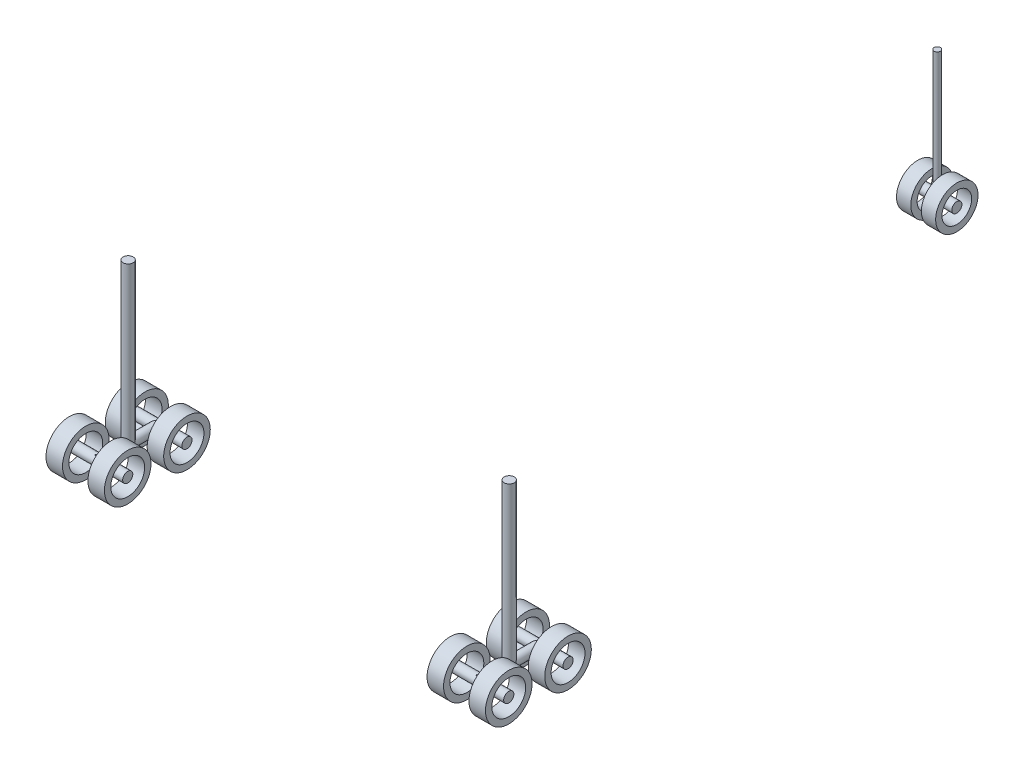
SolidWorks part; units mm, degrees
other "DetailItem1" parameters "RD1"=24.5989, "RD3"=24384, "RD4"=17538.8642, "RD5"=2725.3831, "RD6"=31107.4169, "RD7"=56568.0005, "RD2"=22.452, "RD8"=19.396
ref_plane "Front Plane" through (0, 0, 0) normal (0, 0, 1) x (1, 0, 0)
ref_plane "Top Plane" through (0, 0, 0) normal (0, 1, 0) x (1, 0, 0)
ref_plane "Right Plane" through (0, 0, 0) normal (1, 0, 0) x (0, 0, -1)
sketch "Sketch2" plane through (0, 0, 0) normal (0, 1, 0) x (1, 0, 0)
  line L0 (0, -6122.228) -> (0, 2040.7427)
  line L1 (0, 0) -> (-18096.1342, 0) construction
  line L2 (0, 0) -> (-21640.8, -16307.5125) construction
  line L3 (-21640.8, -18450.2946) -> (-21640.8, -15593.2518)
  line L4 (-21640.8, -15593.2518) -> (0, 2040.7427)
  line L5 (-21640.8, -18450.2946) -> (0, -6122.228)
  line L6 (-9083.802, -5361.1886) -> (-9083.802, -6845.1358) construction
  line L7 (-9083.802, -6845.1358) -> (-9083.802, -11296.9774) construction
  line L8 (-9083.802, -6845.1358) -> (0, -6845.1358) construction
  line L9 (0, 408.1485) -> (-18440.4, -13713.752)
  line L10 (0, -35661.6) -> (-7316.724, -42249.6079) construction
  line L11 (0, -35661.6) -> (-8167.6786, -35661.6) construction
  line L12 (0, -34539.0879) -> (0, -39029.1363)
  line L13 (-7316.724, -43428.2455) -> (-7316.724, -41856.7287)
  line L14 (-7316.724, -41856.7287) -> (0, -34539.0879)
  line L15 (0, -39029.1363) -> (-7316.724, -43428.2455)
  line L16 (-2544.3607, -37083.7674) -> (-2544.3607, -37952.5526) construction
  line L17 (-2544.3607, -37952.5526) -> (-2544.3607, -40558.9084) construction
  line L18 (-2544.3607, -37952.5526) -> (0, -37952.5526) construction
  line L19 (-18440.4, -13713.752) -> (-18440.4, -15898.787)
  line L20 (-18440.4, -15898.787) -> (0, -4489.6339)
  line L21 (0, 408.1485) -> (0, -4489.6339) construction
  line L22 (0, -4489.6339) -> (0, 408.1485) construction
  line L23 (0, 408.1485) -> (0, -2040.7427) construction
  line L24 (0, 408.1485) -> (0, -4489.6339) construction
  line L25 (0, -2040.7427) -> (-18440.4, -14806.2695) construction
  line L26 (0, 408.1485) -> (-21640.8, -16164.6603) construction
  line L27 (-6975.7046, -4933.9377) -> (-6975.7046, -6869.7347) construction
  line L28 (-6975.7046, -6869.7347) -> (-6975.7046, -8805.5317) construction
  line L29 (-6975.7046, -6869.7347) -> (0, -6869.7347) construction
  dimension "Wing Sweep" = 37
  dimension "Half Span" = 21640.8
  dimension "Wing Root" = 8162.9707
  dimension "D4" = 2040.7427
  dimension "Wing Tip" = 2857.0428
  dimension "D6" = 714.2607
  dimension "Wing YBar" = 9083.802
  dimension "Tail Sweep" = 42
  dimension "Tail Root" = 4490.0484
  dimension "D10" = 1122.5121
  dimension "Tail Tip" = 1571.5168
  dimension "D12" = 392.8792
  dimension "D13" = 7316.724
  dimension "Tail Ybar" = 2544.3607
  dimension "First Spar" = 1632.5941
  dimension "Second Spar" = 6530.3766
  dimension "Fuel Tip" = 2185.035
  dimension "Tip Spar" = 571.4086
  dimension "Fuel Ybar" = 6975.7046
  dimension "Fuel Tank Length" = 18440.4
  dimension "Tail Arm" = 35661.6
sketch "Sketch4" plane through (0, 0, 0) normal (0, 1, 0) x (1, 0, 0)
  line L0 (0, 17538.8642) -> (0, -40677.9358) construction
  line L1 (-2194.56, 17538.8642) -> (2194.56, 17538.8642) construction
  line L2 (-2194.56, 10955.1842) -> (-2194.56, -31899.6958)
  line L3 (-2194.56, -40677.9358) -> (2194.56, -40677.9358) construction
  line L4 (2194.56, 10955.1842) -> (2194.56, -31899.6958)
  line L5 (0, -6122.228) -> (0, 2040.7427) construction
  line L6 (-9083.802, -6845.1358) -> (0, -6845.1358) construction
  line L7 (-2544.3607, -37952.5526) -> (0, -37952.5526) construction
  line L8 (0, 0) -> (-21640.8, -16307.5125) construction
  line L9 (-21640.8, -15593.2518) -> (0, 2040.7427) construction
  line L10 (-8474.964, 1555.5245) -> (-5807.964, 1555.5245)
  line L11 (-8474.964, 1555.5245) -> (-8474.964, -5453.2245)
  line L12 (-8474.964, -5453.2245) -> (-5807.964, -5453.2245)
  line L13 (-5807.964, 1555.5245) -> (-5807.964, -5453.2245)
  line L14 (2194.56, 10955.1842) -> (-2194.56, 10955.1842)
  arc A0 (-2194.56, -31899.6958) -> (2194.56, -31899.6958) centre (0, -31899.6958) ccw construction
  spline S0 degree 2 poles (-2194.56, 10955.1842) (-2319.3121, 14550.827) (0, 17538.8642) knots 0 0 0 1 1 1 construction
  spline S1 degree 2 poles (2194.56, 10955.1842) (2319.3121, 14550.827) (0, 17538.8642) knots 0 0 0 1 1 1 construction
  spline S2 degree 3 poles (-2194.56, -31899.6958) (-2185.0252, -17343.0176) (-1882.3736, -55849.4008) (-475.0937, -22625.7195) (0, -39029.1363) knots 0 0 0 0 0.566127 1 1 1 1 construction
  spline S3 degree 3 poles (2194.56, -31899.6958) (2185.0252, -17343.0176) (1882.3736, -55849.4008) (475.0937, -22625.7195) (0, -39029.1363) knots 0 0 0 0 0.566127 1 1 1 1 construction
  spline S4 degree 2 poles (-2194.56, -31899.6958) (-4104.2514, -24790.3016) (0, -27753.3552) knots 0 0 0 1 1 1
  spline S5 degree 2 poles (2194.56, -31899.6958) (4104.2514, -24790.3016) (0, -27753.3552) knots 0 0 0 1 1 1
  point P6 (0, 10955.1842)
  point P7 (0, -31899.6958)
  point P8 (0, -6845.1358)
  point P15 (0, -34094.2558)
  point P28 (-7141.464, 1555.5245)
  point P29 (-7141.464, -3778.4755)
  point P35 (-7141.464, -5381.4791)
  point P43 (0, -1968.3358)
  point P44 (-7141.464, -1247.9751)
  dimension "Fuse Length" = 58216.8
  dimension "Fuse Dia" = 4389.12
  dimension "D3" = 6583.68
  dimension "D4" = 8778.24
  dimension "D6" = 7141.464
  dimension "Engine Dia" = 2667
  dimension "Engine Length" = 7008.749
  dimension "D9" = 5334
  dimension "D10" = 2803.4996
  dimension "D11" = 5597.1607
  dimension "D2" = 19507.2
ref_plane "Plane1" through (0, 609.6, 0) normal (0, 1, 0) x (1, 0, 0)
sketch "Sketch10" plane through (0, 0, 0) normal (0, 1, 0) x (1, 0, 0)
  line L0 (-21640.8, -15593.2518) -> (-2194.56, 252.5066)
  line L1 (-2194.56, 10955.1842) -> (-2194.56, -31899.6958) construction
  line L2 (-21640.8, -15593.2518) -> (-21640.8, -18450.2946)
  line L3 (-21640.8, -18450.2946) -> (-7141.464, -10190.49)
  line L4 (-7141.464, -10190.49) -> (-2194.56, -10190.49)
  line L5 (-21640.8, -18450.2946) -> (0, -6122.228) construction
  line L6 (-21640.8, -15593.2518) -> (0, 2040.7427) construction
  line L7 (-2194.56, -10190.49) -> (-2194.56, 252.5066) construction
  line L9 (0, 271.2873) -> (0, -10190.49)
  line L10 (0, -10190.49) -> (-2194.56, -10190.49)
  line L11 (0, -6122.228) -> (0, 2040.7427) construction
  line L12 (-2194.56, 252.5066) -> (0, 2040.7427)
  line L13 (0, 2040.7427) -> (0, 271.2873)
sketch "Sketch11" plane through (0, 0, 0) normal (0, 1, 0) x (1, 0, 0)
  line L0 (0, 17538.8642) -> (0, -40677.9358) construction
  point P0 (0, -3278.9758)
  dimension "D1" = 20817.84
ref_plane "Plane3" through (0, 1731.482, 0) normal (0, 1, 0) x (1, 0, 0)
sketch "Sketch12" plane through (0, 0, 0) normal (0, 1, 0) x (1, 0, 0)
  line L0 (0, 17538.8642) -> (0, -40677.9358) construction
  line L1 (-127, 11129.9847) -> (127, 11129.9847) construction
  line L2 (-127, 11129.9847) -> (-127, 10780.3837) construction
  line L3 (-127, 10780.3837) -> (127, 10780.3837) construction
  line L4 (127, 11129.9847) -> (127, 10780.3837) construction
  line L5 (-127, 11129.9847) -> (127, 10780.3837) construction
  line L6 (-127, 10780.3837) -> (127, 11129.9847) construction
  line L7 (-4572, -3888.5758) -> (0, 10955.1842) construction
  line L8 (-4876.8, -3469.0546) -> (-4267.2, -3469.0546) construction
  line L9 (-4876.8, -3469.0546) -> (-4876.8, -4308.097) construction
  line L10 (-4876.8, -4308.097) -> (-4267.2, -4308.097) construction
  line L11 (-4267.2, -3469.0546) -> (-4267.2, -4308.097) construction
  line L12 (-4876.8, -3469.0546) -> (-4267.2, -4308.097) construction
  line L13 (-4876.8, -4308.097) -> (-4267.2, -3469.0546) construction
  line L14 (-4572, -3888.5758) -> (0, -3888.5758) construction
  line L15 (-4572, -3888.5758) -> (0, -5296.7893) construction
  line L16 (-4572, -3469.0546) -> (-4572, -4308.097) construction
  line L17 (-4572, -3888.5758) -> (-762, -3888.5758) construction
  line L19 (-1389.4421, -4752.1758) -> (-134.5579, -4752.1758) construction
  line L20 (-1389.4421, -4752.1758) -> (-1389.4421, -3024.9758) construction
  line L21 (-1389.4421, -3024.9758) -> (-134.5579, -3024.9758) construction
  line L22 (-134.5579, -4752.1758) -> (-134.5579, -3024.9758) construction
  line L23 (-1389.4421, -4752.1758) -> (-134.5579, -3024.9758) construction
  line L24 (-1389.4421, -3024.9758) -> (-134.5579, -4752.1758) construction
  circle A0 centre (-4572, -3888.5758) radius 121.92
  circle A1 centre (-1389.4421, -4752.1758) radius 711.2 construction
  circle A4 centre (-1389.4421, -3024.9758) radius 711.2 construction
  point P0 (0, 10955.1842)
  point P7 (-4572, -3888.5758)
  point P30 (-1389.4421, -3736.1758)
  point P31 (-1389.4421, -4040.9758)
  point P39 (-762, -3888.5758)
  dimension "D8" = 243.84
  dimension "D9" = 304.8
  dimension "D11" = 1422.4
  dimension "D1" = 4572
  dimension "D2" = 90
  dimension "D3" = 36
  dimension "D4" = 36
  dimension "D5" = 254
  dimension "D6" = 609.6
  dimension "D7" = 609.6
  dimension "D10" = 36
  dimension "D12" = 3810
ref_plane "Plane2" through (-4572, 0, 3888.5758) normal (0.2944, 0, -0.9557) x (-0.9557, 0, -0.2944)
sketch "Sketch13" plane through (0, 1731.482, 0) normal (0, 1, 0) x (1, 0, 0)
  line L1 (0, -6122.228) -> (0, 2040.7427) construction
  point P0 (0, -3278.9758)
  dimension "D1" = 0
sketch "Sketch14" plane through (-4572, 0, 3888.5758) normal (0.2944, 0, -0.9557) x (-0.9557, 0, -0.2944)
  line L0 (0, 0) -> (-4189.9906, 1731.482) construction
  line L1 (0, 0) -> (-5277.159, 0) construction
  dimension "D1" = 22.452
ref_plane "Plane4" through (-4572, 0, 0) normal (-1, 0, 0) x (0, 0, 1)
sketch "Sketch15" plane through (-4572, 0, 0) normal (-1, 0, 0) x (0, 0, 1)
  line L0 (3888.5758, 0) -> (3278.9758, 1731.482) construction
  line L1 (3888.5758, 0) -> (3888.5758, 1731.482) construction
ref_plane "Plane5" through (-4876.8, 0, 0) normal (1, 0, 0) x (0, 0, -1)
sketch "Sketch16" plane through (-4876.8, 0, 0) normal (1, 0, 0) x (0, 0, -1)
  line L0 (-3888.5758, 0) -> (-3177.3758, 0) construction
  line L2 (-3888.5758, 0) -> (-3888.5758, 631.3043) construction
  line L3 (-3888.5758, 0) -> (-4599.7758, 0) construction
  circle A0 centre (-3177.3758, 0) radius 558.8
  circle A1 centre (-4599.7758, 0) radius 558.8
  circle A3 centre (-3177.3758, 0) radius 406.4
  circle A4 centre (-4599.7758, 0) radius 406.4
  point P3 (-4040.9758, 0)
  point P8 (-3888.5758, 0)
  point P9 (-3736.1758, 0)
  dimension "D1" = 1117.6
  dimension "D3" = 812.8
  dimension "D2" = 304.8
extrude "Boss-Extrude1" add sketch "Sketch16" against normal blind 396.24
ref_plane "Plane6" through (-4572, 0, 0) normal (1, 0, 0) x (0, 0, -1)
mirror "Mirror2" about plane through (-4572, 0, 0) normal (1, 0, 0) of bodies 132 133
extrude "Boss-Extrude2" add sketch "Sketch12" along normal blind 3810
sketch "Sketch17" plane through (-5273.04, 0, 0) normal (-1, 0, 0) x (0, 0, 1)
  circle A0 centre (3177.3758, 0) radius 121.92
  circle A1 centre (3177.3758, 0) radius 406.4 construction
  circle A2 centre (4599.7758, 0) radius 121.92
  circle A3 centre (4599.7758, 0) radius 406.4 construction
  dimension "D1" = 243.84
extrude "Boss-Extrude3" add sketch "Sketch17" against normal up to surface (1402.08 mm away) separate body up to face at (-3870.96, 0, 5006.1758)
ref_plane "Plane7" through (0, 0, 3888.5758) normal (0, 0, 1) x (1, 0, 0)
sketch "Sketch18" plane through (0, 0, 3888.5758) normal (0, 0, 1) x (1, 0, 0)
  circle A0 centre (-4572, 0) radius 121.92
  dimension "D1" = 243.84
extrude "Boss-Extrude4" add sketch "Sketch18" along normal blind 762 and the other way blind 762
ref_plane "Plane8" through (-127, 0, 0) normal (1, 0, 0) x (0, 0, -1)
sketch "Sketch19" plane through (-127, 0, 0) normal (1, 0, 0) x (0, 0, -1)
  line L0 (11129.9847, 0) -> (10780.3837, 0) construction
  circle A0 centre (10955.1842, 0) radius 508
  circle A1 centre (10955.1842, 0) radius 355.6
  dimension "D1" = 1016
  dimension "D2" = 711.2
extrude "Boss-Extrude5" add sketch "Sketch19" against normal blind 342.9 separate body
mirror "Mirror4" about plane through (0, 0, 0) normal (1, 0, 0) of bodies 141 133 132 135 140 134
sketch "Sketch20" plane through (-469.9, 0, 0) normal (-1, 0, 0) x (0, 0, 1)
  circle A0 centre (-10955.1842, 0) radius 121.92
  circle A1 centre (3177.3758, 0) radius 121.92 construction
  circle A2 centre (-10955.1842, 0) radius 355.6 construction
extrude "Boss-Extrude6" add sketch "Sketch20" against normal up to surface (939.8 mm away) separate body up to face at (469.9, 0, -11310.7842)
sketch "Sketch21" plane through (0, 0, 0) normal (0, 1, 0) x (1, 0, 0)
  circle A0 centre (0, 10955.1842) radius 76.2
extrude "Boss-Extrude7" add sketch "Sketch21" along normal blind 3048
sketch "Sketch23" plane through (0, 3810, 0) normal (0, 1, 0) x (1, 0, 0)
  circle A0 centre (0, -3278.9758) radius 469.6531 construction
  point P0 (0, -3278.9758)
  point P3 (0, -3278.9758)
sketch "Sketch24" plane through (-469.9, 0, 0) normal (-1, 0, 0) x (0, 0, 1)
  line L0 (-10955.1842, 0) -> (-10955.1842, 3048) construction
  line L1 (-10878.9842, 3048) -> (-11031.3842, 3048) construction
sketch "Sketch25" plane through (0, 0, 0) normal (0, 1, 0) x (1, 0, 0)
  line L0 (-762, -4015.5758) -> (-762, -3761.5758) construction
  line L1 (-4572, -3888.5758) -> (0, -3888.5758) construction
  line L2 (-762, -3888.5758) -> (-4572, -3888.5758) construction
  line L3 (0, -2402.84) -> (0, 2402.84) construction
  line L4 (762, -3888.5758) -> (4572, -3888.5758) construction
  line L5 (762, -4015.5758) -> (762, -3761.5758) construction
  line L6 (0, 10955.1842) -> (0, 14003.1842) construction
  line L7 (-298.45, 14003.1842) -> (0, 14003.1842) construction
  line L8 (0, 14003.1842) -> (298.45, 14003.1842) construction
  line L9 (127, 14511.1842) -> (127, 13495.1842) construction
  line L10 (127, 14511.1842) -> (469.9, 14511.1842) construction
  line L11 (127, 13495.1842) -> (469.9, 13495.1842) construction
  line L12 (469.9, 14511.1842) -> (469.9, 13495.1842) construction
  line L13 (127, 14511.1842) -> (469.9, 13495.1842) construction
  line L14 (127, 13495.1842) -> (469.9, 14511.1842) construction
  line L15 (-127, 14511.1842) -> (-127, 13495.1842) construction
  line L16 (-127, 14511.1842) -> (-469.9, 14511.1842) construction
  line L17 (-127, 13495.1842) -> (-469.9, 13495.1842) construction
  line L18 (-469.9, 14511.1842) -> (-469.9, 13495.1842) construction
  line L19 (-127, 14511.1842) -> (-469.9, 13495.1842) construction
  line L20 (-127, 13495.1842) -> (-469.9, 14511.1842) construction
  circle A0 centre (-762, -3202.7758) radius 558.8 construction
  circle A1 centre (-762, -4574.3758) radius 558.8 construction
  circle A2 centre (762, -4574.3758) radius 558.8 construction
  circle A3 centre (762, -3202.7758) radius 558.8 construction
  point P4 (-762, -4015.5758)
  point P5 (-762, -3888.5758)
  point P6 (-762, -3761.5758)
  point P27 (762, -3761.5758)
  point P28 (762, -4015.5758)
  point P31 (0, 0)
  dimension "D1" = 1117.6
  dimension "D5" = 254
  dimension "D2" = 254
  dimension "D3" = 3810
  dimension "D4" = 3048
  dimension "D6" = 1016
  dimension "D7" = 342.9
sketch "Sketch26" plane through (0, 0, 0) normal (1, 0, 0) x (0, 0, -1)
  line L0 (10955.1842, 3048) -> (13999.0661, 3206.389) construction
  line L1 (11031.3842, 3048) -> (10878.9842, 3048) construction
  circle A0 centre (14507.0661, 3206.389) radius 508 construction
  point P4 (0, 0)
  point P9 (13999.0661, 3206.389)
  dimension "D1" = 1016
  dimension "D2" = 3048
equation "\"D6@Sketch2\" = \"Wing Tip@Sketch2\" / 4"
equation "\"D4@Sketch2\" = \"Wing Root@Sketch2\" / 4"
equation "\"D10@Sketch2\" = \"Tail Root@Sketch2\" / 4"
equation "\"D12@Sketch2\" = \"Tail Tip@Sketch2\" / 4"
equation "\"D13@Sketch2\"=48.01/2"
equation "\"First Spar@Sketch2\"=0.2 * \"Wing Root@Sketch2\""
equation "\"Second Spar@Sketch2\"    = 0.8 * \"Wing Root@Sketch2\""
equation "\"Tip Spar@Sketch2\"=0.2 * \"Wing Tip@Sketch2\""
equation "\"D3@Sketch4\" = 1.5 * \"Fuse Dia@Sketch4\""
equation "\"D4@Sketch4\" = 2 * \"Fuse Dia@Sketch4\""
equation "\"D6@Sketch4\" = 0.33 * \"Half Span@Sketch2\""
equation "\"D9@Sketch4\" = 2 * \"Engine Dia@Sketch4\""
equation "\"D10@Sketch4\" = 0.40 * \"Engine Length@Sketch4\""
